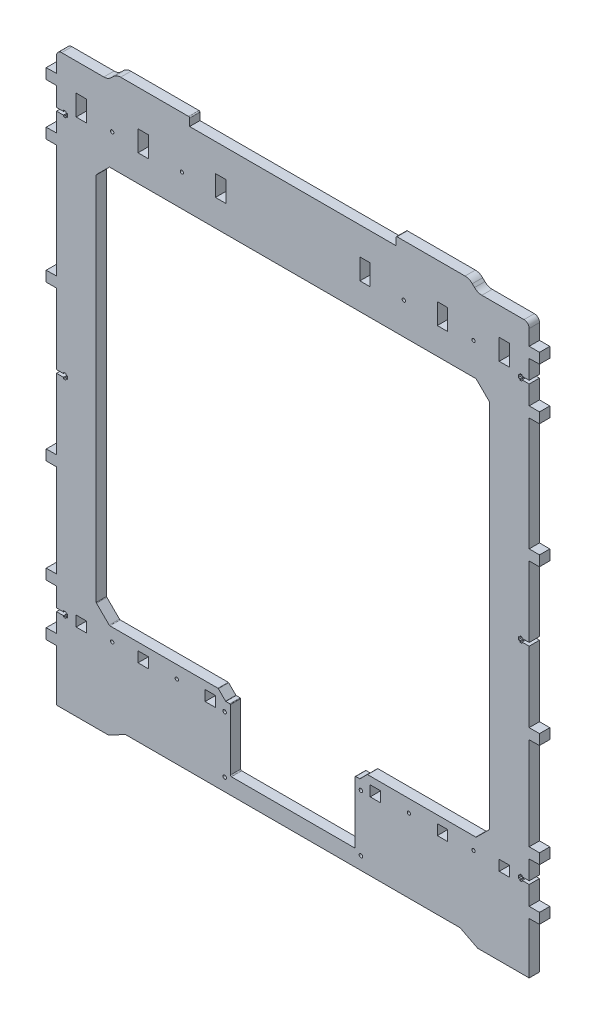
SolidWorks part; units mm, degrees
ref_plane "Front" through (0, 0, 0) normal (0, 0, 1) x (1, 0, 0)
ref_plane "Top" through (0, 0, 0) normal (0, 1, 0) x (1, 0, 0)
ref_plane "Right" through (0, 0, 0) normal (1, 0, 0) x (0, 0, -1)
sketch "Эскиз1" plane through (0, 0, 0) normal (0, 0, 1) x (1, 0, 0)
  line L0 (162, -270.3) -> (179, -279)
  line L1 (-162, -270.3) -> (162, -270.3)
  line L2 (-179, -279) -> (-162, -270.3)
  line L3 (-229, -279) -> (-179, -279)
  line L4 (-229, -229.1) -> (-229, -279)
  line L5 (-238.9986, -229.0666) -> (-229, -229.1)
  line L6 (-238.9986, -219.0666) -> (-238.9986, -229.0666)
  line L7 (-229, -218.9) -> (-238.9986, -219.0666)
  line L8 (-229, -200.55) -> (-229, -218.9)
  line L9 (-222.2, -200.55) -> (-229, -200.55)
  line L10 (-222.2, -201.75) -> (-222.2, -200.55)
  line L11 (-220, -201.75) -> (-222.2, -201.75)
  line L12 (-220, -200.55) -> (-220, -201.75)
  line L13 (-218.5, -200.55) -> (-220, -200.55)
  line L14 (-218.5, -197.45) -> (-218.5, -200.55)
  line L15 (-220, -197.45) -> (-218.5, -197.45)
  line L16 (-220, -196.25) -> (-220, -197.45)
  line L17 (-222.2, -196.25) -> (-220, -196.25)
  line L18 (-222.2, -197.45) -> (-222.2, -196.25)
  line L19 (-229, -197.45) -> (-222.2, -197.45)
  line L20 (-229, -179.1) -> (-229, -197.45)
  line L21 (-238.9986, -179.0666) -> (-229, -179.1)
  line L22 (-238.9986, -169.0666) -> (-238.9986, -179.0666)
  line L23 (-229, -168.9) -> (-238.9986, -169.0666)
  line L24 (-229, -79.1) -> (-229, -168.9)
  line L25 (-238.9986, -79.0666) -> (-229, -79.1)
  line L26 (-238.9986, -69.0666) -> (-238.9986, -79.0666)
  line L27 (-229, -68.9) -> (-238.9986, -69.0666)
  line L28 (-229, -0.55) -> (-229, -68.9)
  line L29 (-222.2, -0.55) -> (-229, -0.55)
  line L30 (-222.2, -1.75) -> (-222.2, -0.55)
  line L31 (-220, -1.75) -> (-222.2, -1.75)
  line L32 (-220, -0.55) -> (-220, -1.75)
  line L33 (-218.5, -0.55) -> (-220, -0.55)
  line L34 (-218.5, 2.55) -> (-218.5, -0.55)
  line L35 (-220, 2.55) -> (-218.5, 2.55)
  line L36 (-220, 3.75) -> (-220, 2.55)
  line L37 (-222.2, 3.75) -> (-220, 3.75)
  line L38 (-222.2, 2.55) -> (-222.2, 3.75)
  line L39 (-229, 2.55) -> (-222.2, 2.55)
  line L40 (-229, 70.9) -> (-229, 2.55)
  line L41 (-238.9986, 70.9334) -> (-229, 70.9)
  line L42 (-238.9986, 80.9334) -> (-238.9986, 70.9334)
  line L43 (-229, 81.1) -> (-238.9986, 80.9334)
  line L44 (-229, 190.9) -> (-229, 81.1)
  line L45 (-238.9986, 190.9334) -> (-229, 190.9)
  line L46 (-238.9986, 200.9334) -> (-238.9986, 190.9334)
  line L47 (-229, 201.1) -> (-238.9986, 200.9334)
  line L48 (-229, 219.45) -> (-229, 201.1)
  line L49 (-222.2, 219.45) -> (-229, 219.45)
  line L50 (-222.2, 218.25) -> (-222.2, 219.45)
  line L51 (-220, 218.25) -> (-222.2, 218.25)
  line L52 (-220, 219.45) -> (-220, 218.25)
  line L53 (-218.5, 219.45) -> (-220, 219.45)
  line L54 (-218.5, 222.55) -> (-218.5, 219.45)
  line L55 (-220, 222.55) -> (-218.5, 222.55)
  line L56 (-220, 223.75) -> (-220, 222.55)
  line L57 (-222.2, 223.75) -> (-220, 223.75)
  line L58 (-222.2, 222.55) -> (-222.2, 223.75)
  line L59 (-229, 222.55) -> (-222.2, 222.55)
  line L60 (-229, 240.9) -> (-229, 222.55)
  line L61 (-238.9986, 240.9334) -> (-229, 240.9)
  line L62 (-238.9986, 250.9334) -> (-238.9986, 240.9334)
  line L63 (-229, 251.1) -> (-238.9986, 250.9334)
  line L64 (-229, 266) -> (-229, 251.1)
  line L65 (-183.1421, 271) -> (-224, 271)
  line L66 (-173.9289, 276.0711) -> (-176.0711, 273.9289)
  line L67 (-101, 279) -> (-166.8579, 279)
  line L68 (-100, 271) -> (-100, 278)
  line L69 (100, 271) -> (-100, 271)
  line L70 (100, 278) -> (100, 271)
  line L71 (166.8579, 279) -> (101, 279)
  line L72 (176.0711, 273.9289) -> (173.9289, 276.0711)
  line L73 (224, 271) -> (183.1421, 271)
  line L74 (229, 251.1) -> (229, 266)
  line L75 (238.9986, 251.0666) -> (229, 251.1)
  line L76 (238.9986, 241.0666) -> (238.9986, 251.0666)
  line L77 (229, 240.9) -> (238.9986, 241.0666)
  line L78 (229, 222.55) -> (229, 240.9)
  line L79 (222.2, 222.55) -> (229, 222.55)
  line L80 (222.2, 223.75) -> (222.2, 222.55)
  line L81 (220, 223.75) -> (222.2, 223.75)
  line L82 (220, 222.55) -> (220, 223.75)
  line L83 (218.5, 222.55) -> (220, 222.55)
  line L84 (218.5, 219.45) -> (218.5, 222.55)
  line L85 (220, 219.45) -> (218.5, 219.45)
  line L86 (220, 218.25) -> (220, 219.45)
  line L87 (222.2, 218.25) -> (220, 218.25)
  line L88 (222.2, 219.45) -> (222.2, 218.25)
  line L89 (229, 219.45) -> (222.2, 219.45)
  line L90 (229, 201.1) -> (229, 219.45)
  line L91 (238.9986, 201.0666) -> (229, 201.1)
  line L92 (238.9986, 191.0666) -> (238.9986, 201.0666)
  line L93 (229, 190.9) -> (238.9986, 191.0666)
  line L94 (229, 81.1) -> (229, 190.9)
  line L95 (238.9986, 81.0666) -> (229, 81.1)
  line L96 (238.9986, 71.0666) -> (238.9986, 81.0666)
  line L97 (229, 70.9) -> (238.9986, 71.0666)
  line L98 (229, 2.55) -> (229, 70.9)
  line L99 (222.2, 2.55) -> (229, 2.55)
  line L100 (222.2, 3.75) -> (222.2, 2.55)
  line L101 (220, 3.75) -> (222.2, 3.75)
  line L102 (220, 2.55) -> (220, 3.75)
  line L103 (218.5, 2.55) -> (220, 2.55)
  line L104 (218.5, -0.55) -> (218.5, 2.55)
  line L105 (220, -0.55) -> (218.5, -0.55)
  line L106 (220, -1.75) -> (220, -0.55)
  line L107 (222.2, -1.75) -> (220, -1.75)
  line L108 (222.2, -0.55) -> (222.2, -1.75)
  line L109 (229, -0.55) -> (222.2, -0.55)
  line L110 (229, -68.9) -> (229, -0.55)
  line L111 (238.9986, -68.9334) -> (229, -68.9)
  line L112 (238.9986, -78.9334) -> (238.9986, -68.9334)
  line L113 (229, -79.1) -> (238.9986, -78.9334)
  line L114 (229, -168.9) -> (229, -79.1)
  line L115 (238.9986, -168.9334) -> (229, -168.9)
  line L116 (238.9986, -178.9334) -> (238.9986, -168.9334)
  line L117 (229, -179.1) -> (238.9986, -178.9334)
  line L118 (229, -197.45) -> (229, -179.1)
  line L119 (222.2, -197.45) -> (229, -197.45)
  line L120 (222.2, -196.25) -> (222.2, -197.45)
  line L121 (220, -196.25) -> (222.2, -196.25)
  line L122 (220, -197.45) -> (220, -196.25)
  line L123 (218.5, -197.45) -> (220, -197.45)
  line L124 (218.5, -200.55) -> (218.5, -197.45)
  line L125 (220, -200.55) -> (218.5, -200.55)
  line L126 (220, -201.75) -> (220, -200.55)
  line L127 (222.2, -201.75) -> (220, -201.75)
  line L128 (222.2, -200.55) -> (222.2, -201.75)
  line L129 (229, -200.55) -> (222.2, -200.55)
  line L130 (229, -218.9) -> (229, -200.55)
  line L131 (238.9986, -218.9334) -> (229, -218.9)
  line L132 (238.9986, -228.9334) -> (238.9986, -218.9334)
  line L133 (229, -229.1) -> (238.9986, -228.9334)
  line L134 (229, -279) -> (229, -229.1)
  line L135 (179, -279) -> (229, -279)
  line L136 (-65, 224) -> (-75, 224)
  line L137 (-65, 244.1) -> (-65, 224)
  line L138 (-75, 244.1) -> (-65, 244.1)
  line L139 (-75, 224) -> (-75, 244.1)
  line L140 (75, 244.1) -> (75, 224)
  line L141 (65, 244.1) -> (75, 244.1)
  line L142 (65, 224) -> (65, 244.1)
  line L143 (75, 224) -> (65, 224)
  line L144 (-140, 224) -> (-150, 224)
  line L145 (-140, 244.1) -> (-140, 224)
  line L146 (-150, 244.1) -> (-140, 244.1)
  line L147 (-150, 224) -> (-150, 244.1)
  line L148 (150, 244.1) -> (150, 224)
  line L149 (140, 244.1) -> (150, 244.1)
  line L150 (140, 224) -> (140, 244.1)
  line L151 (150, 224) -> (140, 224)
  line L152 (-200, 224) -> (-210, 224)
  line L153 (-200, 244.1) -> (-200, 224)
  line L154 (-210, 244.1) -> (-200, 244.1)
  line L155 (-210, 224) -> (-210, 244.1)
  line L156 (210, 244.1) -> (210, 224)
  line L157 (200, 244.1) -> (210, 244.1)
  line L158 (200, 224) -> (200, 244.1)
  line L159 (210, 224) -> (200, 224)
  line L160 (-75, -204.0023) -> (-85, -204.0023)
  line L161 (-75, -193.9023) -> (-75, -204.0023)
  line L162 (-85, -193.9023) -> (-75, -193.9023)
  line L163 (-85, -204.0023) -> (-85, -193.9023)
  line L164 (85, -193.9023) -> (85, -204.0023)
  line L165 (75, -193.9023) -> (85, -193.9023)
  line L166 (75, -204.0023) -> (75, -193.9023)
  line L167 (85, -204.0023) -> (75, -204.0023)
  line L168 (150, -193.9023) -> (150, -204.0023)
  line L169 (140, -193.9023) -> (150, -193.9023)
  line L170 (140, -204.0023) -> (140, -193.9023)
  line L171 (150, -204.0023) -> (140, -204.0023)
  line L172 (-140, -204.0023) -> (-150, -204.0023)
  line L173 (-140, -193.9023) -> (-140, -204.0023)
  line L174 (-150, -193.9023) -> (-140, -193.9023)
  line L175 (-150, -204.0023) -> (-150, -193.9023)
  line L176 (-200, -204.0023) -> (-210, -204.0023)
  line L177 (-200, -193.9023) -> (-200, -204.0023)
  line L178 (-210, -193.9023) -> (-200, -193.9023)
  line L179 (-210, -204.0023) -> (-210, -193.9023)
  line L180 (210, -193.9023) -> (210, -204.0023)
  line L181 (200, -193.9023) -> (210, -193.9023)
  line L182 (200, -204.0023) -> (200, -193.9023)
  line L183 (210, -204.0023) -> (200, -204.0023)
  line L184 (190.4196, -173.4149) -> (190.4196, 184.9554)
  line L185 (190.1242, 185.665) -> (177.831, 197.8717)
  line L186 (-190.5276, -173.4149) -> (-190.5276, 184.9554)
  line L187 (-190.2322, 185.665) -> (-177.9389, 197.8717)
  line L188 (177.1264, 198.1621) -> (-177.2343, 198.1621)
  line L189 (190.1242, -174.1245) -> (177.831, -186.3311)
  line L190 (-190.2322, -174.1245) -> (-177.9389, -186.3311)
  line L213 (-72.1908, -186.7679) -> (-65.2029, -193.7559)
  line L214 (72.078, -186.7679) -> (65.09, -193.7559)
  line L215 (60.4436, -194.4023) -> (60.4436, -253.4023)
  line L216 (59.4436, -254.4023) -> (-59.5564, -254.4023)
  line L217 (-60.5564, -253.4023) -> (-60.5564, -194.4023)
  line L218 (-64.8493, -193.9023) -> (-61.0564, -193.9023)
  line L219 (60.9436, -193.9023) -> (64.7365, -193.9023)
  line L220 (-177.2343, -186.6215) -> (-72.5443, -186.6215)
  line L221 (177.1264, -186.6215) -> (72.4315, -186.6215)
  arc A0 (-224, 271) -> (-229, 266) centre (-224, 266) ccw
  arc A1 (-183.1421, 271) -> (-176.0711, 273.9289) centre (-183.1421, 281) ccw
  arc A2 (-166.8579, 279) -> (-173.9289, 276.0711) centre (-166.8579, 269) ccw
  arc A3 (-100, 278) -> (-101, 279) centre (-101, 278) ccw
  arc A4 (101, 279) -> (100, 278) centre (101, 278) ccw
  arc A5 (173.9289, 276.0711) -> (166.8579, 279) centre (166.8579, 269) ccw
  arc A6 (176.0711, 273.9289) -> (183.1421, 271) centre (183.1421, 281) ccw
  arc A7 (229, 266) -> (224, 271) centre (224, 266) ccw
  circle A8 centre (107.5, 229.05) radius 1.6
  circle A9 centre (112.5, -198.9523) radius 1.6
  circle A10 centre (-107.5, 229.05) radius 1.6
  circle A11 centre (-112.5, -198.9523) radius 1.6
  circle A12 centre (-175, -198.9523) radius 1.6
  circle A13 centre (175, 229.05) radius 1.6
  circle A14 centre (-175, 229.05) radius 1.6
  circle A15 centre (175, -198.9523) radius 1.6
  arc A16 (-190.5276, -173.4149) -> (-190.2322, -174.1245) centre (-189.5276, -173.4149) ccw
  arc A17 (-177.9389, -186.3311) -> (-177.2343, -186.6215) centre (-177.2343, -185.6215) ccw
  arc A18 (190.1242, -174.1245) -> (190.4196, -173.4149) centre (189.4196, -173.4149) ccw
  arc A19 (177.1264, -186.6215) -> (177.831, -186.3311) centre (177.1264, -185.6215) ccw
  arc A20 (177.831, 197.8717) -> (177.1264, 198.1621) centre (177.1264, 197.1621) ccw
  arc A21 (190.4196, 184.9554) -> (190.1242, 185.665) centre (189.4196, 184.9554) ccw
  arc A22 (-177.2343, 198.1621) -> (-177.9389, 197.8717) centre (-177.2343, 197.1621) ccw
  arc A23 (-190.2322, 185.665) -> (-190.5276, 184.9554) centre (-189.5276, 184.9554) ccw
  circle A43 centre (-66.0564, -203.1023) radius 1.7
  circle A44 centre (-66.0564, -257.9023) radius 1.7
  circle A45 centre (65.9436, -257.9023) radius 1.7
  circle A46 centre (65.9436, -203.1023) radius 1.7
  arc A47 (-60.5564, -253.4023) -> (-59.5564, -254.4023) centre (-59.5564, -253.4023) ccw
  arc A48 (59.4436, -254.4023) -> (60.4436, -253.4023) centre (59.4436, -253.4023) ccw
  arc A49 (-72.1908, -186.7679) -> (-72.5443, -186.6215) centre (-72.5443, -187.1215) ccw
  arc A50 (-65.2029, -193.7559) -> (-64.8493, -193.9023) centre (-64.8493, -193.4023) ccw
  arc A51 (-60.5564, -194.4023) -> (-61.0564, -193.9023) centre (-61.0564, -194.4023) ccw
  arc A52 (72.4315, -186.6215) -> (72.078, -186.7679) centre (72.4315, -187.1215) ccw
  arc A53 (64.7365, -193.9023) -> (65.09, -193.7559) centre (64.7365, -193.4023) ccw
  arc A54 (60.9436, -193.9023) -> (60.4436, -194.4023) centre (60.9436, -194.4023) ccw
extrude "Бобышка-Вытянуть1" add sketch "Эскиз1" along normal blind 10
